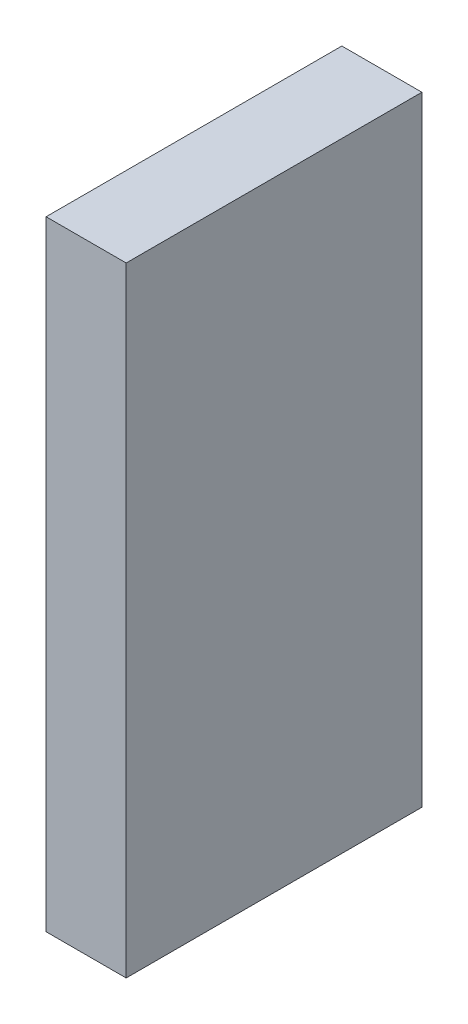
SolidWorks part; units mm, degrees
ref_plane "Alzado" through (0, 0, 0) normal (0, 0, 1) x (1, 0, 0)
ref_plane "Planta" through (0, 0, 0) normal (0, 1, 0) x (1, 0, 0)
ref_plane "Vista lateral" through (0, 0, 0) normal (1, 0, 0) x (0, 0, -1)
sketch "Croquis1" plane through (0, 0, 0) normal (1, 0, 0) x (0, 0, -1)
  line L1 (0, 0) -> (55.4, 0)
  line L2 (0, 0) -> (0, 116)
  line L3 (0, 116) -> (55.4, 116)
  line L4 (55.4, 0) -> (55.4, 116)
  dimension "D1" = 116
  dimension "D2" = 55.4
extrude "Saliente-Extruir1" add sketch "Croquis1" along normal blind 15
